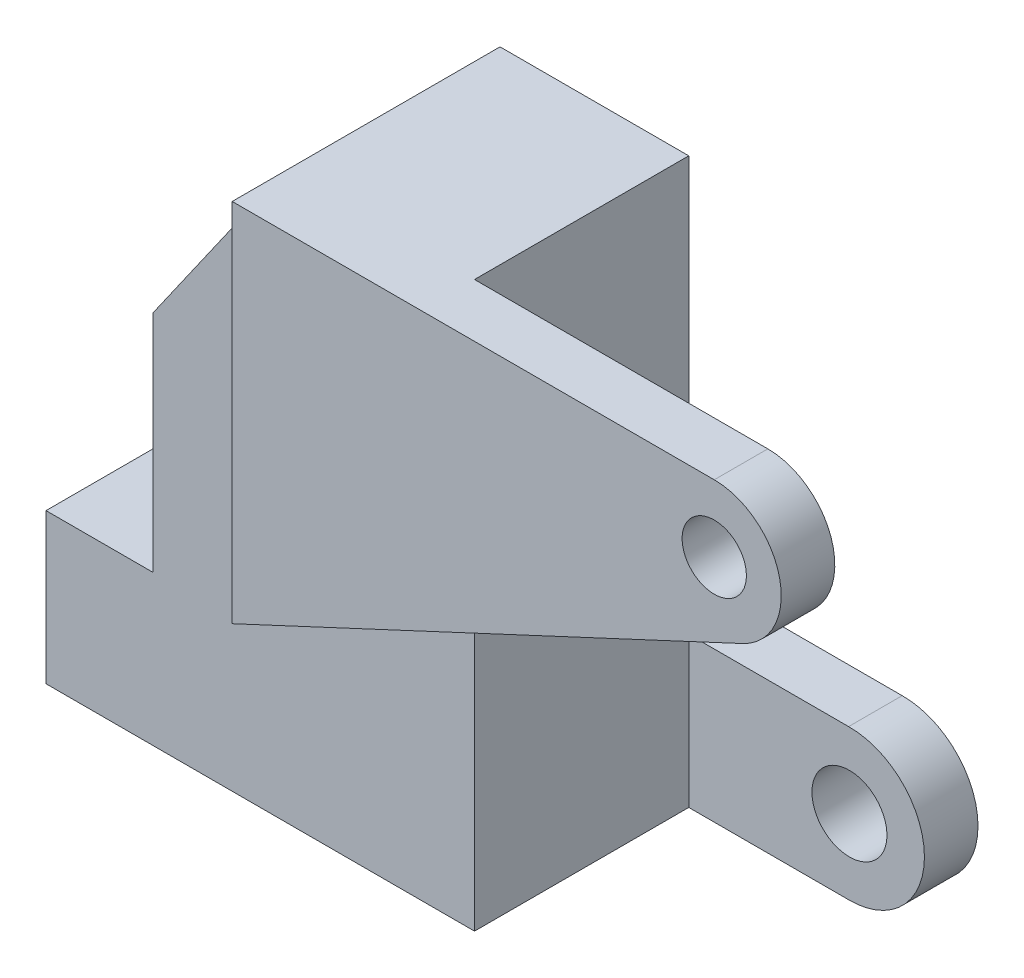
SolidWorks part; units mm, degrees
ref_plane "Płaszczyzna przednia" through (0, 0, 0) normal (0, 0, 1) x (1, 0, 0)
ref_plane "Płaszczyzna górna" through (0, 0, 0) normal (0, 1, 0) x (1, 0, 0)
ref_plane "Płaszczyzna prawa" through (0, 0, 0) normal (1, 0, 0) x (0, 0, -1)
sketch "Szkic1" plane through (0, 0, 0) normal (0, 0, 1) x (1, 0, 0)
  line L0 (0, 0) -> (40, 0)
  line L1 (40, 0) -> (40, 52.6814)
  line L2 (40, 52.6814) -> (22.3807, 52.6814)
  line L3 (22.3807, 52.6814) -> (10, 35)
  line L4 (10, 35) -> (10, 14)
  line L5 (10, 14) -> (0, 14)
  line L6 (0, 14) -> (0, 0)
  dimension "D1" = 10
  dimension "D2" = 40
  dimension "D3" = 35
  dimension "D4" = 35
  dimension "D5" = 52.6814
  dimension "D6" = 14
extrude "Dodanie-wyciągnięcie1" add sketch "Szkic1" along normal blind 20
sketch "Szkic2" plane through (0, 0, 0) normal (0, 0, -1) x (-1, 0, 0)
  line L2 (0, 0) -> (-40, 0) construction
  line L3 (-10, 0) -> (-10, 14)
  line L4 (-40, 0) -> (-40, 52.6814) construction
  line L5 (-54.9223, 14) -> (-10, 14)
  line L7 (-54.9223, 0.0009) -> (-10, 0)
  line L8 (-10, 35) -> (-10, 14) construction
  circle A1 centre (-55, 7.0004) radius 3.5
  arc A3 (-54.9223, 14) -> (-54.9223, 0.0009) centre (-55, 7.0004) ccw
  point P15 (0, 0)
  dimension "D1" = 7
  dimension "D4" = 6.9996
  dimension "D3" = 7
  dimension "D2" = 15
extrude "Dodanie-wyciągnięcie2" add sketch "Szkic2" along normal blind 5
sketch "Szkic3" plane through (0, 0, 20) normal (0, 0, 1) x (1, 0, 0)
  line L0 (22.3807, 52.6814) -> (22.3807, 18.5469)
  line L1 (22.3807, 18.5469) -> (70.0229, 40.7629)
  line L2 (67.3807, 52.6814) -> (22.3807, 52.6814)
  arc A0 (70.0229, 40.7629) -> (67.3807, 52.6814) centre (67.3807, 46.4292) ccw
  circle A1 centre (67.3807, 46.4292) radius 3
  dimension "D2" = 6
  dimension "D1" = 45
  dimension "D3" = 6.2522
  dimension "D4" = 65
extrude "Dodanie-wyciągnięcie3" add sketch "Szkic3" along normal blind 5
